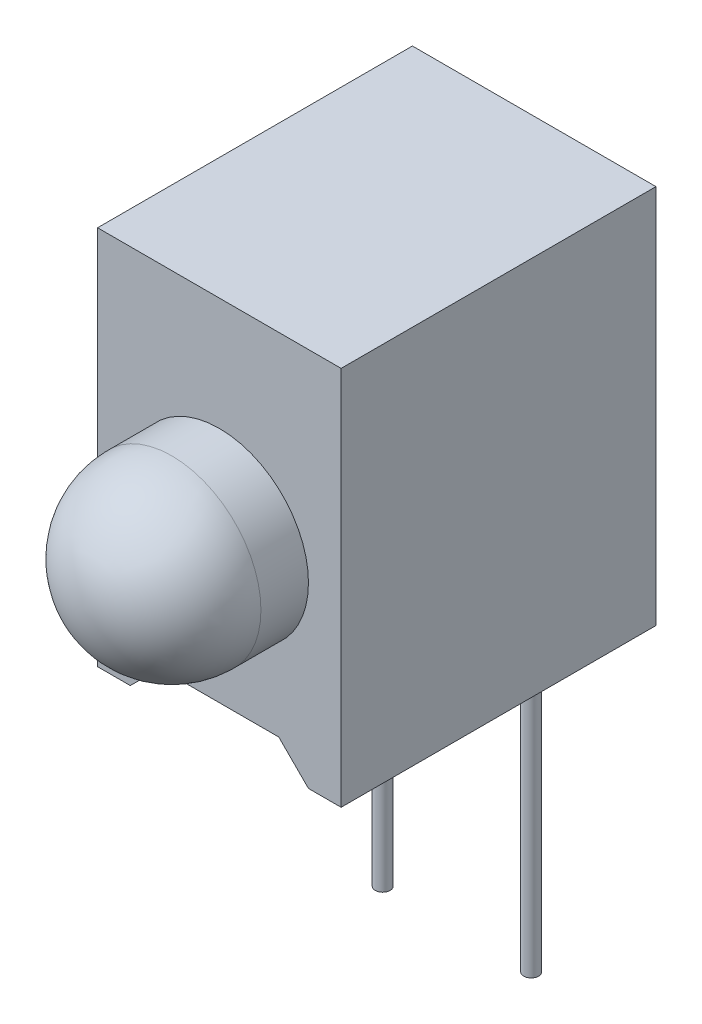
SolidWorks part; units mm, degrees
ref_plane "Front" through (0, 0, 0) normal (0, 0, 1) x (1, 0, 0)
ref_plane "Top" through (0, 0, 0) normal (0, 1, 0) x (1, 0, 0)
ref_plane "Right" through (0, 0, 0) normal (1, 0, 0) x (0, 0, -1)
sketch "Sketch1" plane through (0, 0, 0) normal (0, 0, 1) x (1, 0, 0)
  line L1 (-1, 0.5) -> (1, 0.5)
  line L2 (2.05, 6.4) -> (-2.05, 6.4)
  line L3 (2.05, 6.4) -> (2.05, 0)
  line L4 (2.05, 0) -> (1.5, 0)
  line L5 (-2.05, 6.4) -> (-2.05, 0)
  line L6 (-1.5, 0) -> (-1, 0.5)
  line L7 (1, 0.5) -> (1.5, 0)
  line L8 (-1.5, 0) -> (-2.05, 0)
  line L9 (-1.5, 0) -> (1.5, 0) construction
  point P9 (0, 0)
  dimension "D1" = 6.4
  dimension "D2" = 4.1
  dimension "D3" = 3
  dimension "D4" = 135
  dimension "D5" = 135
  dimension "D6" = 0.5
  dimension "D7" = 0.55
extrude "Extrude1" add sketch "Sketch1" against normal blind 5.3
sketch "Sketch2" plane through (0, 0, 0) normal (0, 0, 1) x (1, 0, 0)
  line L0 (0, 0) -> (0, 6.8471) construction
  circle A0 centre (0, 3) radius 1.5
  dimension "D2" = 3
  dimension "D1" = 3
extrude "Extrude2" add sketch "Sketch2" along normal blind 2.3
fillet "Fillet1" radius 1.5
sketch "Sketch3" plane through (0, 0.5, 0) normal (0, -1, 0) x (1, 0, 0)
  line L0 (-2.5166, -4) -> (2.6475, -4) construction
  line L1 (-1, -5.3) -> (1, -5.3) construction
  line L2 (0, 0) -> (0, -5.5824) construction
  circle A0 centre (1.25, -4) radius 0.125
  circle A1 centre (-1.25, -4) radius 0.125
  dimension "D2" = 0.25
  dimension "D1" = 1.3
  dimension "D3" = 2.5
extrude "Extrude3" add sketch "Sketch3" along normal blind 5.3
